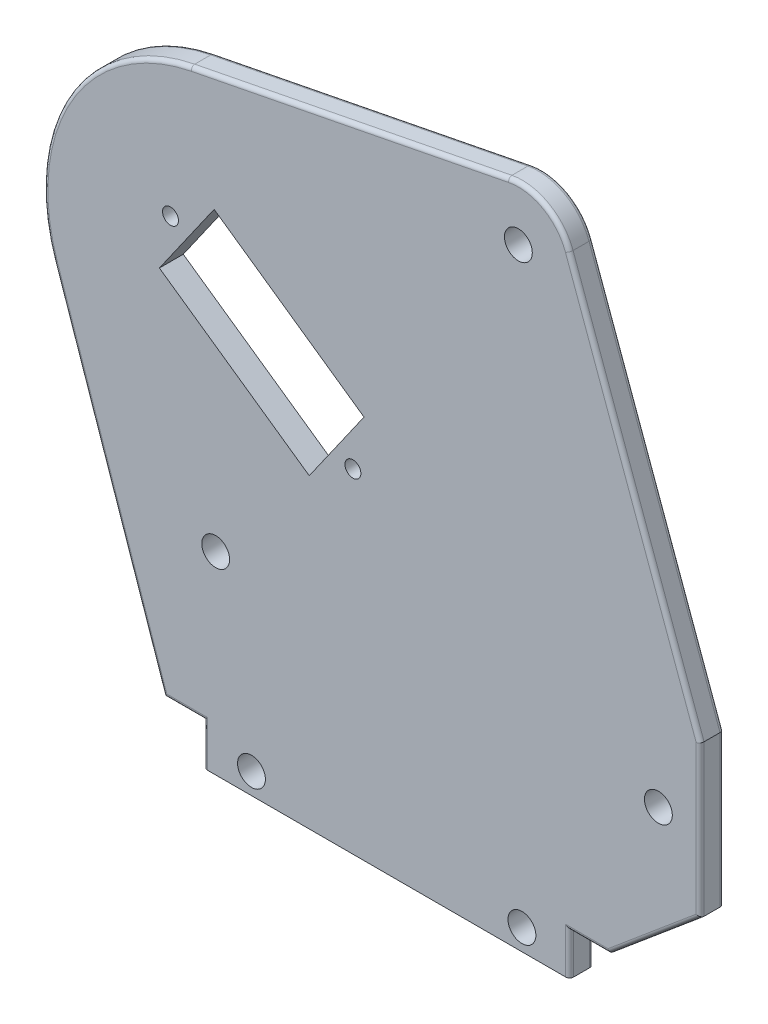
SolidWorks part; units mm, degrees
ref_plane "Front Plane" through (0, 0, 0) normal (0, 0, 1) x (1, 0, 0)
ref_plane "Top Plane" through (0, 0, 0) normal (0, 1, 0) x (1, 0, 0)
ref_plane "Right Plane" through (0, 0, 0) normal (1, 0, 0) x (0, 0, -1)
sketch "Sketch1" plane through (0, 0, 0) normal (0, 0, 1) x (1, 0, 0)
  line L0 (0, 0) -> (0, 28420.5788) construction
  line L1 (0, 0) -> (-28420.5788, 0) construction
  line L2 (-23, 10) -> (-28, 10)
  line L3 (-23, 0) -> (23, 0)
  line L4 (-23, 0) -> (-23, 10)
  line L5 (-23, 10) -> (23, 10) construction
  line L6 (23, 0) -> (23, 10)
  line L7 (-28, 10) -> (-41.8608, 50.4677)
  line L8 (-24.6313, 80.3256) -> (15.2446, 88.1625)
  line L9 (23, 10) -> (28, 10)
  line L10 (28, 10) -> (39.4051, 19.57)
  line L11 (39.4051, 19.57) -> (39.4051, 38.57)
  line L12 (39.4051, 38.57) -> (22.9346, 83.8223)
  line L13 (-20.22, 57.88) -> (-41.0516, 204.4066) construction
  line L14 (16.5541, 81.5) -> (-4.2776, 228.0266) construction
  line L15 (-75.8246, 230.8844) -> (-41.0516, 204.4066) construction
  line L16 (-41.0516, 204.4066) -> (-4.2776, 228.0266) construction
  line L17 (-4.2776, 228.0266) -> (-75.8246, 230.8844) construction
  line L18 (-75.8246, 230.8844) -> (-226.1828, 176.1814) construction
  line L19 (-204.7956, 140.0346) -> (9.2044, 224.1635) construction
  line L20 (-226.1828, 176.1814) -> (-204.7956, 140.0346) construction
  line L21 (-204.7956, 140.0346) -> (-256.0612, 159.9555) construction
  line L22 (-256.0612, 159.9555) -> (-226.1828, 176.1814) construction
  line L23 (-20.22, 57.88) -> (33.1708, 65.9687)
  line L24 (33.1708, 65.9687) -> (9.2044, 224.1635)
  circle A0 centre (-20.22, 57.88) radius 22.875 construction
  circle A1 centre (16.5541, 81.5) radius 6.79 construction
  arc A2 (-41.8608, 50.4677) -> (-24.6313, 80.3256) centre (-20.22, 57.88) cw
  arc A3 (15.2446, 88.1625) -> (22.9346, 83.8223) centre (16.5541, 81.5) cw
  circle A4 centre (-20.22, 57.88) radius 17.5 construction
  circle A5 centre (16.5541, 81.5) radius 7.5 construction
  circle A6 centre (-41.0516, 204.4066) radius 13.1881 construction
  circle A7 centre (-4.2776, 228.0266) radius 8.7345 construction
  circle A8 centre (-75.8246, 230.8844) radius 8.7345 construction
  circle A9 centre (-226.1828, 176.1814) radius 8.1525 construction
  circle A10 centre (-204.7956, 140.0346) radius 9.1166 construction
  dimension "D7" = 45.75
  dimension "D8" = 13.58
  dimension "D14" = 35
  dimension "D15" = 15
  dimension "D1" = 46
  dimension "D2" = 10
  dimension "D3" = 57.88
  dimension "D4" = 20.22
  dimension "D5" = 16.5541
  dimension "D6" = 81.5
  dimension "D9" = 5
  dimension "D10" = 5
  dimension "D11" = 140
  dimension "D12" = 19
  dimension "D13" = 160
  dimension "D16" = 148
  dimension "D17" = 110
  dimension "D18" = 160
  dimension "D19" = 54
  dimension "D20" = 214
  dimension "D21" = 42
  dimension "D22" = 34
  dimension "D23" = 55
  dimension "D24" = 54
  dimension "D25" = 160
sketch "Sketch2" plane through (0, 0, 0) normal (0, 0, 1) x (1, 0, 0)
  line L0 (39.4051, 38.57) -> (22.9346, 83.8223) construction
  line L1 (39.4051, 19.57) -> (39.4051, 38.57) construction
  line L2 (28, 10) -> (39.4051, 19.57) construction
  line L3 (23, 10) -> (28, 10) construction
  line L4 (23, 0) -> (23, 10) construction
  line L5 (-23, 0) -> (23, 0) construction
  line L6 (-23, 0) -> (-23, 10) construction
  line L7 (-23, 10) -> (-28, 10) construction
  line L8 (-28, 10) -> (-41.8608, 50.4677) construction
  line L9 (-24.6313, 80.3256) -> (15.2446, 88.1625) construction
  line L10 (39.4051, 38.57) -> (22.9346, 83.8223)
  line L11 (39.4051, 19.57) -> (39.4051, 38.57)
  line L12 (28, 10) -> (39.4051, 19.57)
  line L13 (23, 10) -> (28, 10)
  line L14 (23, 0) -> (23, 10)
  line L15 (-23, 0) -> (23, 0)
  line L16 (-23, 0) -> (-23, 10)
  line L17 (-23, 10) -> (-28, 10)
  line L18 (-28, 10) -> (-41.8608, 50.4677)
  line L19 (-24.6313, 80.3256) -> (15.2446, 88.1625)
  line L20 (-21.6935, 66.2364) -> (-28.5764, 56.4065)
  line L21 (-21.6935, 66.2364) -> (-2.853, 53.0441)
  line L22 (-28.5764, 56.4065) -> (-9.7359, 43.2143)
  line L23 (-2.853, 53.0441) -> (-9.7359, 43.2143)
  line L24 (-38.9581, 71.0006) -> (37.1704, 17.6948) construction
  line L25 (0, -200000) -> (0, 228420.5788) construction
  arc A0 (22.9346, 83.8223) -> (15.2446, 88.1625) centre (16.5541, 81.5) ccw construction
  arc A1 (-24.6313, 80.3256) -> (-41.8608, 50.4677) centre (-20.22, 57.88) ccw construction
  arc A2 (22.9346, 83.8223) -> (15.2446, 88.1625) centre (16.5541, 81.5) ccw
  arc A3 (-24.6313, 80.3256) -> (-41.8608, 50.4677) centre (-20.22, 57.88) ccw
  circle A4 centre (-27.1828, 62.7554) radius 1
  circle A5 centre (-4.2465, 46.6953) radius 1
  circle A6 centre (17, 7.4) radius 1.75
  circle A7 centre (-17, 7.4) radius 1.75
  circle A8 centre (34.1551, 29.07) radius 1.75
  circle A9 centre (-21.5, 29.07) radius 1.75
  circle A10 centre (16.5541, 81.5) radius 1.75
  point P35 (39.4051, 29.07)
  dimension "D5" = 2
  dimension "D6" = 2
  dimension "D10" = 3.5
  dimension "D1" = 23
  dimension "D2" = 12
  dimension "D3" = 6
  dimension "D4" = 35
  dimension "D7" = 2.5
  dimension "D8" = 2.5
  dimension "D9" = 6
  dimension "D11" = 5.25
  dimension "D12" = 7.4
  dimension "D13" = 6
  dimension "D14" = 6
  dimension "D15" = 21.5
extrude "Boss-Extrude1" add sketch "Sketch2" along normal mid plane 3
fillet "Fillet1" radius 0.5 12 edges at (-34.9304, 30.2339, 1.5) (-40.0329, 69.313, 1.5) (-4.6933, 84.2441, 1.5) (19.8915, 87.4132, 1.5) (-25.5, 10, 1.5) (-23, 5, 1.5) (0, 0, 1.5) (23, 5, 1.5) (25.5, 10, 1.5) (33.7025, 14.785, 1.5) (39.4051, 29.07, 1.5) (31.1698, 61.1962, 1.5)
fillet "Fillet2" radius 0.5 12 edges at (31.1698, 61.1962, -1.5) (19.8915, 87.4132, -1.5) (-34.9304, 30.2339, -1.5) (-40.0329, 69.313, -1.5) (39.4051, 29.07, -1.5) (23, 5, -1.5) (25.5, 10, -1.5) (33.7025, 14.785, -1.5) (0, 0, -1.5) (-23, 5, -1.5) (-25.5, 10, -1.5) (-4.6933, 84.2441, -1.5)
sketch "Sketch3" plane through (0, 0, 1.5) normal (0, 0, 1) x (1, 0, 0)
  line L5 (23, 0) -> (-23, 0) construction
  line L6 (-23, 0) -> (23, 0)
  line L7 (-23, 0) -> (-23, 4.75)
  line L8 (-23, 4.75) -> (23, 4.75)
  line L9 (23, 0) -> (23, 4.75)
  line L10 (23, 10) -> (23, 0) construction
  line L11 (-23, 0) -> (-23, 10) construction
  dimension "D1" = 4.75
extrude "Cut-Extrude1" cut sketch "Sketch3" against normal through all both and the other way through all
